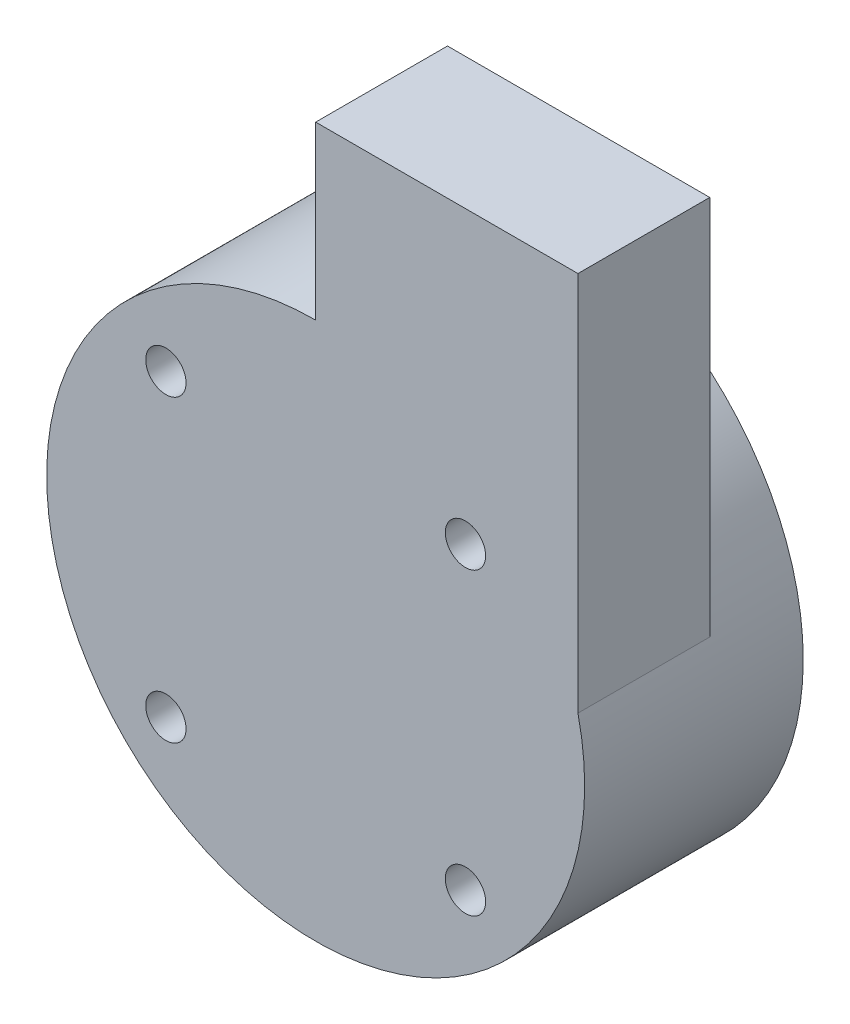
SolidWorks part; units mm, degrees
material "合金钢"
ref_plane "前视基准面" through (0, 0, 0) normal (0, 0, 1) x (1, 0, 0)
ref_plane "上视基准面" through (0, 0, 0) normal (0, 1, 0) x (1, 0, 0)
ref_plane "右视基准面" through (0, 0, 0) normal (1, 0, 0) x (0, 0, -1)
sketch "草图1" plane through (0, 0, 0) normal (0, 0, 1) x (1, 0, 0)
  line L0 (-40.8442, 40.8442) -> (0, 0) construction
  line L1 (0, 0) -> (52.9656, 52.9656) construction
  line L2 (0, 0) -> (64.3042, 0) construction
  circle A0 centre (0, 0) radius 40
  circle A1 centre (0, 0) radius 31.5 construction
  circle A2 centre (-22.2739, 22.2739) radius 3
  circle A3 centre (22.2739, 22.2739) radius 3
  circle A4 centre (22.2739, -22.2739) radius 3
  circle A5 centre (-22.2739, -22.2739) radius 3
  point P18 (0, 0)
  dimension "D1" = 80
  dimension "D4" = 63
  dimension "D5" = 6
  dimension "D2" = 45
  dimension "D3" = 45
  dimension "D6" = 4
extrude "凸台-拉伸1" add sketch "草图1" along normal blind 32.5
sketch "草图3" plane through (0, 0, 0) normal (1, 0, 0) x (0, 0, -1)
  line L0 (-32.5, 40) -> (-32.5, -40) construction
  line L1 (-32.5, 0) -> (-12.9, 0)
  line L2 (-32.5, 0) -> (-32.5, 65.5)
  line L3 (-32.5, 65.5) -> (-12.9, 65.5)
  line L4 (-12.9, 0) -> (-12.9, 65.5)
  line L5 (0, 40) -> (-32.5, 40) construction
  dimension "D1" = 25.5
  dimension "D2" = 19.6
extrude "凸台-拉伸2" add sketch "草图3" along normal blind 39
sketch "草图4" plane through (0, 0, 0) normal (0, 0, 1) x (1, 0, 0)
  line L0 (0, 0) -> (55.4425, 0) construction
  line L1 (0, 0) -> (33.2586, 33.2586) construction
  circle A0 centre (0, 0) radius 31.5 construction
  circle A1 centre (22.2739, 22.2739) radius 3
  dimension "D1" = 63
  dimension "D2" = 6
  dimension "D3" = 45
extrude "切除-拉伸2" cut sketch "草图4" along normal blind 57
sketch "草图5" plane through (0, 0, 32.5) normal (0, 0, 1) x (1, 0, 0)
  point P0 (-8.0879, 81.6992)
